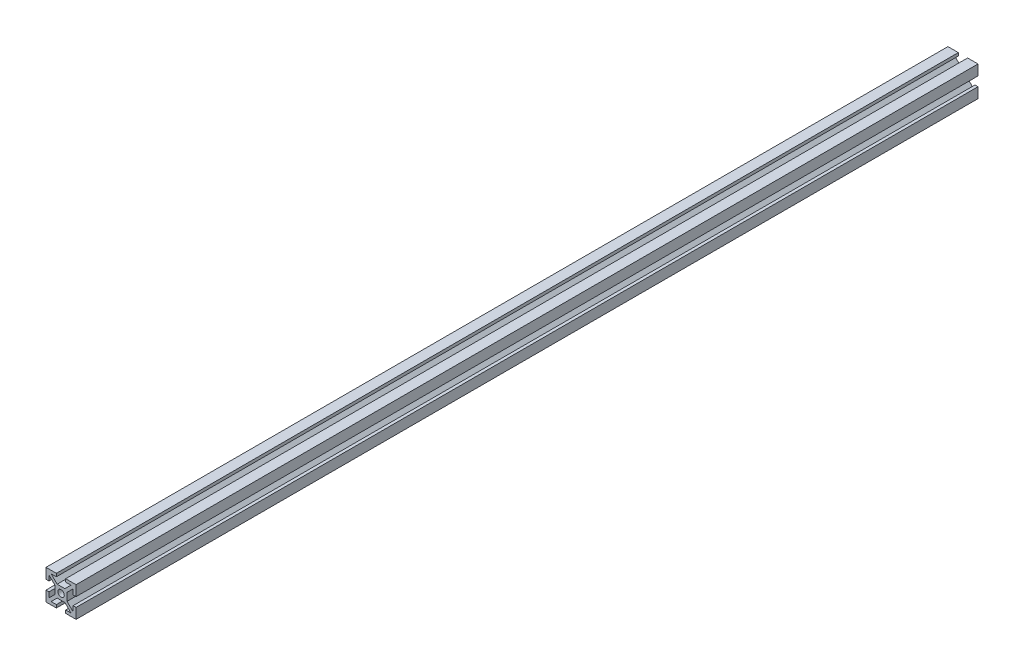
SolidWorks part; units mm, degrees
ref_plane "Plan de face" through (0, 0, 0) normal (0, 0, 1) x (1, 0, 0)
ref_plane "Plan de dessus" through (0, 0, 0) normal (0, 1, 0) x (1, 0, 0)
ref_plane "Plan de droite" through (0, 0, 0) normal (1, 0, 0) x (0, 0, -1)
sketch "Esquisse1" plane through (0, 0, 0) normal (0, 0, 1) x (1, 0, 0)
  line L0 (20, 13.1) -> (18, 13.1)
  line L1 (0, 0) -> (6.9, 0)
  line L2 (0, 0) -> (0, 6.9)
  line L3 (0, 20) -> (6.9, 20)
  line L4 (20, 0) -> (20, 6.9)
  line L5 (18, 13.1) -> (18, 16.5858)
  line L6 (0, 0) -> (20, 20) construction
  line L7 (14, 12.5858) -> (14, 10)
  line L8 (14, 12.5858) -> (18, 16.5858)
  line L9 (13.1, 20) -> (13.1, 18)
  line L10 (13.1, 18) -> (16.5858, 18)
  line L11 (12.5858, 14) -> (16.5858, 18)
  line L12 (12.5858, 14) -> (10, 14)
  line L13 (14, 7.4142) -> (14, 10)
  line L14 (14, 7.4142) -> (18, 3.4142)
  line L15 (18, 6.9) -> (18, 3.4142)
  line L16 (20, 6.9) -> (18, 6.9)
  line L17 (13.1, 2) -> (16.5858, 2)
  line L18 (12.5858, 6) -> (16.5858, 2)
  line L19 (13.1, 0) -> (13.1, 2)
  line L20 (12.5858, 6) -> (10, 6)
  line L21 (7.4142, 6) -> (10, 6)
  line L22 (7.4142, 6) -> (3.4142, 2)
  line L23 (6.9, 2) -> (3.4142, 2)
  line L24 (6.9, 0) -> (6.9, 2)
  line L25 (2, 6.9) -> (2, 3.4142)
  line L26 (6, 7.4142) -> (2, 3.4142)
  line L27 (0, 6.9) -> (2, 6.9)
  line L28 (6, 7.4142) -> (6, 10)
  line L29 (6, 12.5858) -> (6, 10)
  line L30 (6, 12.5858) -> (2, 16.5858)
  line L31 (2, 13.1) -> (2, 16.5858)
  line L32 (0, 13.1) -> (2, 13.1)
  line L33 (6.9, 18) -> (3.4142, 18)
  line L34 (7.4142, 14) -> (3.4142, 18)
  line L35 (6.9, 20) -> (6.9, 18)
  line L36 (7.4142, 14) -> (10, 14)
  line L37 (20, 13.1) -> (20, 20)
  line L38 (13.1, 20) -> (20, 20)
  line L39 (0, 13.1) -> (0, 20)
  line L40 (13.1, 0) -> (20, 0)
  circle A0 centre (10, 10) radius 2.15
  point P51 (10, 10)
  dimension "D2" = 4.3
  dimension "D1" = 20
  dimension "D3" = 2
  dimension "D4" = 6.2
  dimension "D5" = 6
  dimension "D6" = 2
  dimension "D7" = 4
extrude "Boss.-Extru.1" add sketch "Esquisse1" along normal blind 600
